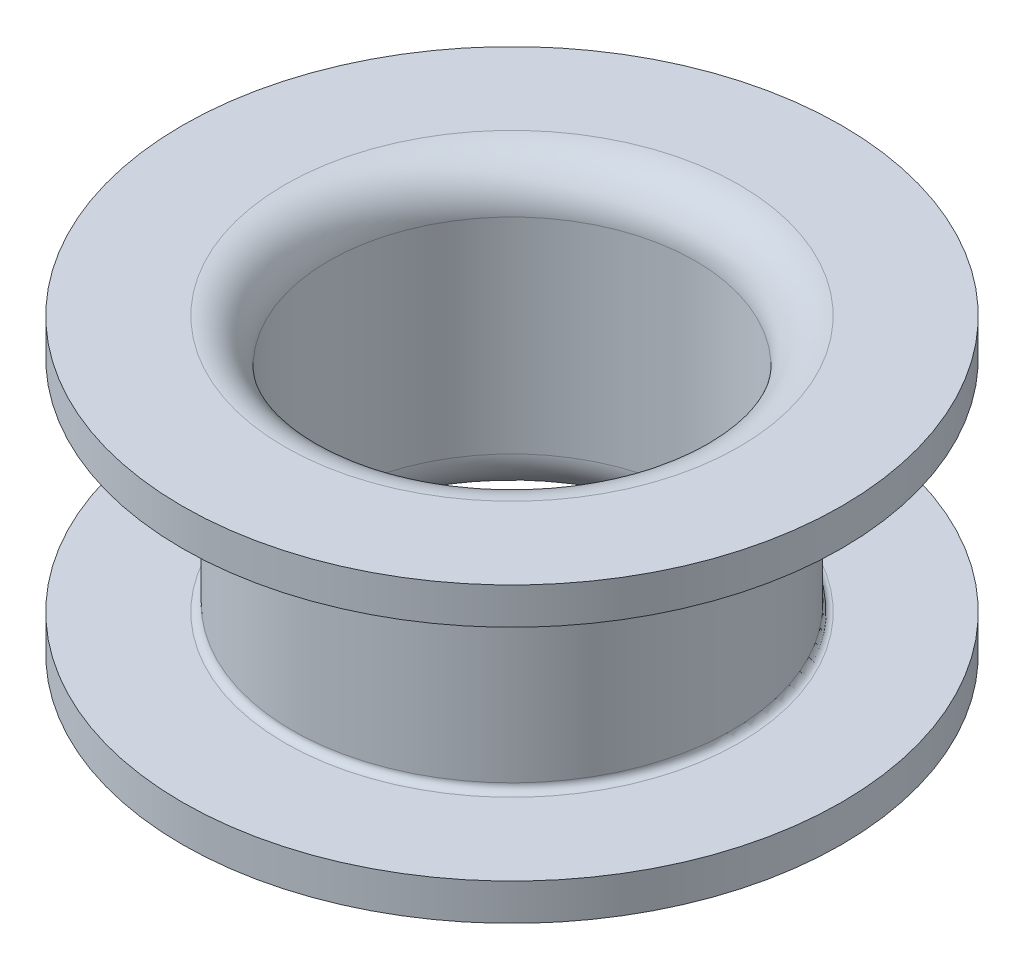
SolidWorks part; units mm, degrees
ref_plane "Plan1" through (0, 0, 0) normal (0, 0, 1) x (1, 0, 0)
ref_plane "Plan2" through (0, 0, 0) normal (0, 1, 0) x (1, 0, 0)
ref_plane "Plan3" through (0, 0, 0) normal (1, 0, 0) x (0, 0, -1)
sketch "Esquisse1" plane through (0, 0, 0) normal (0, 0, 1) x (1, 0, 0)
  line L0 (0, 0) -> (0, 13.4634) construction
  line L1 (6.2, 0) -> (9, 0)
  line L2 (9, 0) -> (9, 1)
  line L3 (9, 1) -> (6.2, 1)
  line L4 (6, 1.2) -> (6, 6.8)
  line L5 (6.2, 7) -> (9, 7)
  line L6 (9, 7) -> (9, 8)
  line L7 (9, 8) -> (6.2, 8)
  line L8 (5, 6.8) -> (5, 1.2)
  arc A0 (6, 6.8) -> (6.2, 7) centre (6.2, 6.8) cw
  arc A1 (6.2, 1) -> (6, 1.2) centre (6.2, 1.2) cw
  arc A2 (5, 6.8) -> (6.2, 8) centre (6.2, 6.8) cw
  arc A3 (6.2, 0) -> (5, 1.2) centre (6.2, 1.2) cw
  dimension "D7" = 0.2
  dimension "D8" = 1.2
  dimension "D1" = 10
  dimension "D2" = 1
  dimension "D3" = 1
  dimension "D4" = 8
  dimension "D5" = 1
  dimension "D6" = 9
revolve "Base-Révolution" add sketch "Esquisse1" angle 360 about L0
